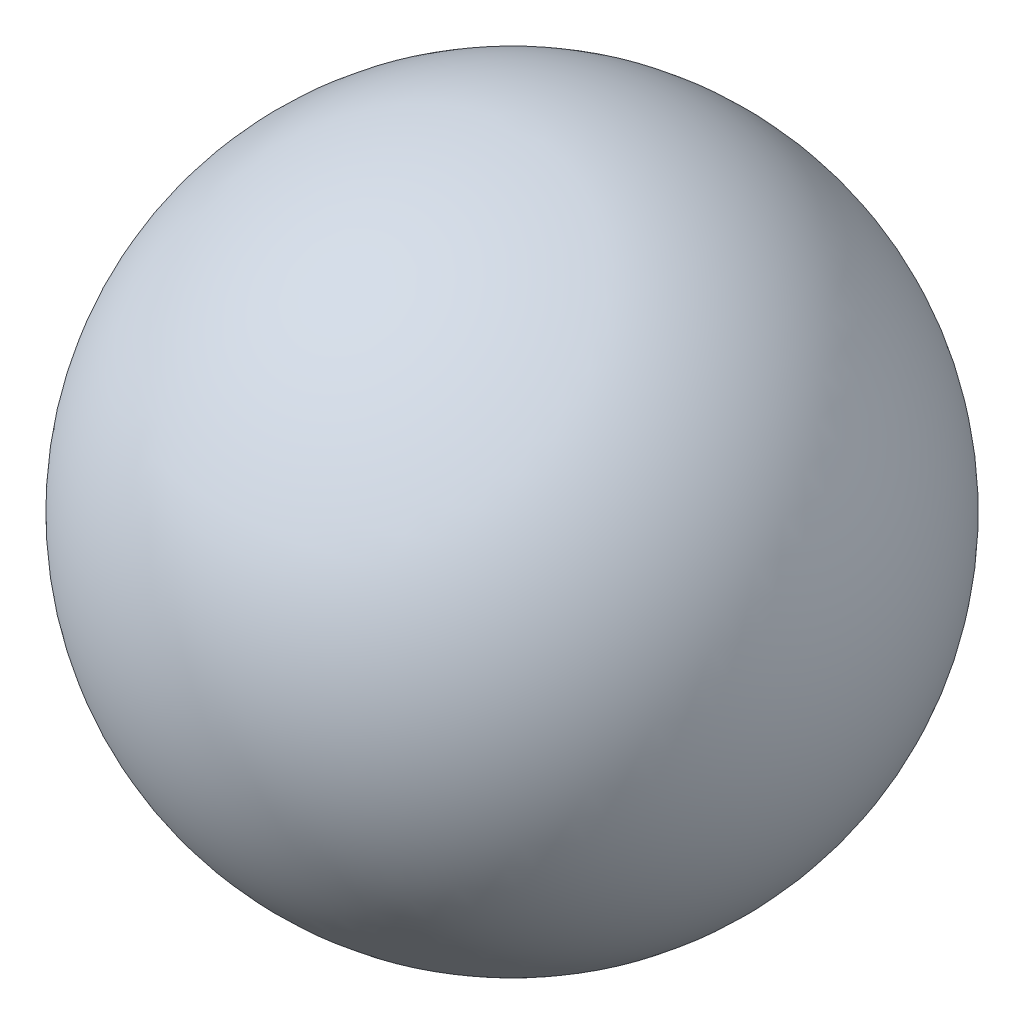
SolidWorks part; units mm, degrees
material "Ti-6Al-2Sn-2Zr-2Mo-2Cr-0.25Si (SS)"
ref_plane "Front Plane" through (0, 0, 0) normal (0, 0, 1) x (1, 0, 0)
ref_plane "Top Plane" through (0, 0, 0) normal (0, 1, 0) x (1, 0, 0)
ref_plane "Right Plane" through (0, 0, 0) normal (1, 0, 0) x (0, 0, -1)
sketch "Sketch1" plane through (0, 0, 0) normal (0, 0, 1) x (1, 0, 0)
  line L0 (0, 373) -> (0, 370)
  line L1 (0, -370) -> (0, -373)
  arc A1 (0, 373) -> (0, -373) centre (0, 0) ccw
  arc A2 (0, 370) -> (0, -370) centre (0, 0) ccw
revolve "Revolve1" add sketch "Sketch1" angle 360 about L1
